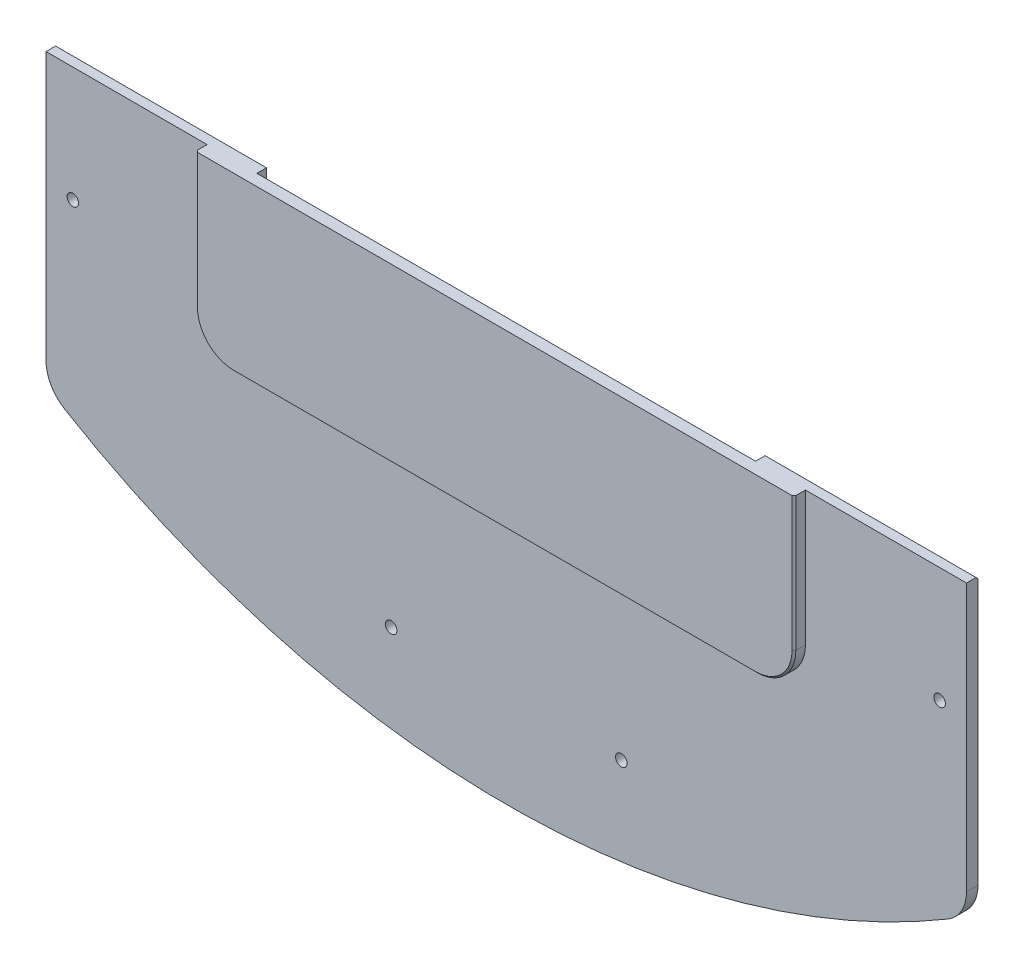
SolidWorks part; units mm, degrees
ref_plane "前视基准面" through (0, 0, 0) normal (0, 0, 1) x (1, 0, 0)
ref_plane "上视基准面" through (0, 0, 0) normal (0, 1, 0) x (1, 0, 0)
ref_plane "右视基准面" through (0, 0, 0) normal (1, 0, 0) x (0, 0, -1)
other "Configuration Table"
sketch "草图1" plane through (0, 0, 0) normal (0, 0, 1) x (1, 0, 0)
  line L1 (-120, -15) -> (120, -15)
  line L2 (-120, -15) -> (-120, -90.3287)
  line L4 (120, -15) -> (120, -90.3287)
  arc A1 (-120, -90.3287) -> (120, -90.3287) centre (0, 100) ccw
  dimension "D3" = 15
  dimension "D5" = 450
  dimension "D2" = 240
  dimension "D4" = 120
  dimension "D6" = 100
extrude "凸台-拉伸1" add sketch "草图1" along normal blind 3
sketch "草图2" plane through (0, 0, 3) normal (0, 0, 1) x (1, 0, 0)
  line L0 (120, -15) -> (-120, -15) construction
  line L1 (-78, -15) -> (78, -15)
  line L2 (-78, -15) -> (-78, -60)
  line L3 (-78, -60) -> (78, -60)
  line L4 (78, -15) -> (78, -60)
  dimension "D1" = 156
  dimension "D2" = 78
  dimension "D3" = 45
extrude "凸台-拉伸2" add sketch "草图2" along normal blind 3
sketch "草图3" plane through (0, 0, 0) normal (0, 0, -1) x (-1, 0, 0)
  line L0 (0, 0) -> (0, -50000) construction
  line L1 (-120, -15) -> (120, -15) construction
  circle A0 centre (30, -100) radius 1.5
  circle A1 centre (113, -45) radius 1.5
  circle A2 centre (-113, -45) radius 1.5
  circle A3 centre (-30, -100) radius 1.5
  dimension "D1" = 30
  dimension "D2" = 3
  dimension "D4" = 3
  dimension "D3" = 85
  dimension "D5" = 113
  dimension "D6" = 30
extrude "切除-拉伸1" cut sketch "草图3" against normal blind 3
sketch "草图4" plane through (0, 0, 0) normal (0, 0, -1) x (-1, 0, 0)
  line L0 (-120, -15) -> (120, -15) construction
  line L1 (-65, -15) -> (65, -15)
  line L2 (-65, -15) -> (-65, -35)
  line L3 (-65, -35) -> (65, -35)
  line L4 (65, -15) -> (65, -35)
  dimension "D1" = 130
  dimension "D2" = 65
  dimension "D3" = 20
extrude "切除-拉伸2" cut sketch "草图4" against normal blind 3
fillet "圆角1" radius 10 2 edges at (120, -90.3287, 1.5) (-120, -90.3287, 1.5)
chamfer "倒角1" distance 0.5 angle 45 5 edges at (92.5, -15, 0) (-92.5, -15, 0) (-65, -25, 0) (65, -25, 0) (0, -35, 0)
fillet "圆角2" radius 10 2 edges at (-78, -60, 4.5) (78, -60, 4.5)
chamfer "倒角2" distance 0.5 angle 45 5 edges at (78, -32.5, 6) (75.0711, -57.0711, 6) (-78, -32.5, 6) (0, -60, 6) (-75.0711, -57.0711, 6)
